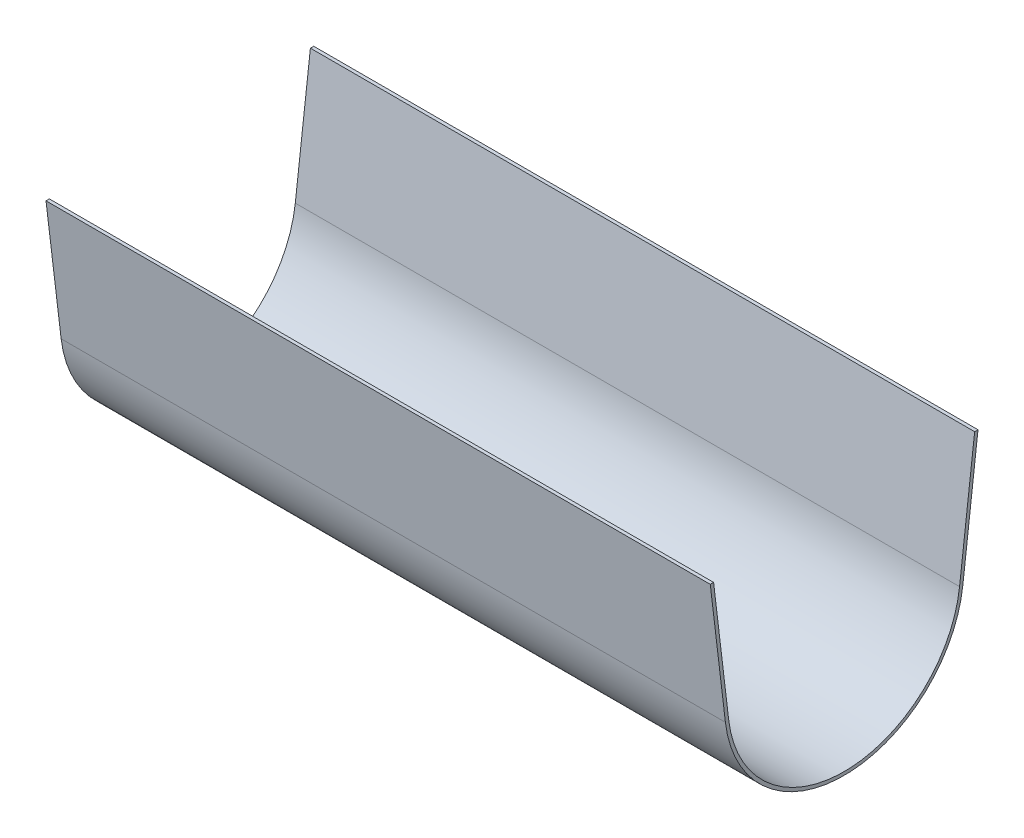
SolidWorks part; units mm, degrees
material "Silicon Rubber"
ref_plane "Front Plane" through (0, 0, 0) normal (0, 0, 1) x (1, 0, 0)
ref_plane "Top Plane" through (0, 0, 0) normal (0, 1, 0) x (1, 0, 0)
ref_plane "Right Plane" through (0, 0, 0) normal (1, 0, 0) x (0, 0, -1)
sketch "Sketch1" plane through (0, 0, 0) normal (1, 0, 0) x (0, 0, -1)
  line L0 (0, 0) -> (50000, 0) construction
  line L3 (-40.305, 0) -> (-35.7472, -38.2586)
  line L4 (40.305, 0) -> (35.7472, -38.2586)
  line L5 (-39.2979, 0) -> (-34.7543, -38.1403)
  line L6 (39.2979, 0) -> (34.7543, -38.1403)
  line L7 (-40.305, 0) -> (-39.2979, 0)
  line L8 (-39.312, 0.1183) -> (-34.7543, -38.1403) construction
  line L9 (40.305, 0) -> (39.2979, 0)
  line L10 (39.312, 0.1183) -> (34.7543, -38.1403) construction
  arc A0 (-35.7472, -38.2586) -> (35.7472, -38.2586) centre (0, -34) ccw
  arc A1 (-34.7543, -38.1403) -> (34.7543, -38.1403) centre (0, -34) ccw
  point P0 (0, -70)
  dimension "D4" = 70
  dimension "D3" = 35
  dimension "D2" = 80.61
  dimension "D1" = 1
extrude "Boss-Extrude1" add sketch "Sketch1" along normal mid plane 200
